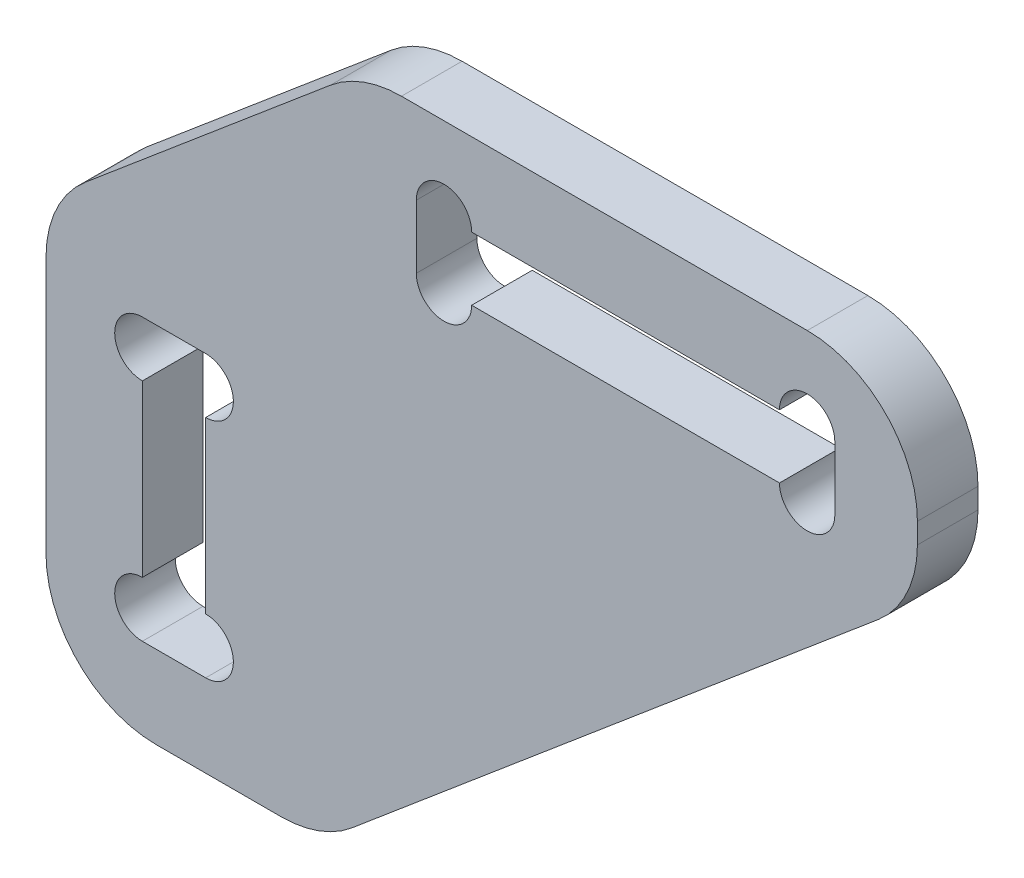
SolidWorks part; units mm, degrees
material "Thornel Mat VMA"
ref_plane "前视基准面" through (0, 0, 0) normal (0, 0, 1) x (1, 0, 0)
ref_plane "上视基准面" through (0, 0, 0) normal (0, 1, 0) x (1, 0, 0)
ref_plane "右视基准面" through (0, 0, 0) normal (1, 0, 0) x (0, 0, -1)
sketch "草图1" plane through (0, 0, 0) normal (0, 0, 1) x (1, 0, 0)
  line L0 (-9.6, 4.15) -> (10.6, 4.15)
  line L1 (7.6, -1.15) -> (-7.6, -1.15)
  line L2 (7.6, -1.15) -> (7.6, 1.15)
  line L3 (7.6, 1.15) -> (-7.6, 1.15)
  line L4 (-7.6, -1.15) -> (-7.6, 1.15)
  line L5 (7.6, -1.15) -> (-7.6, 1.15) construction
  line L6 (7.6, 1.15) -> (-7.6, -1.15) construction
  line L7 (-15.25, -17.7) -> (-17.55, -17.7)
  line L8 (-15.25, -17.7) -> (-15.25, -7.5)
  line L9 (-15.25, -7.5) -> (-17.55, -7.5)
  line L10 (-17.55, -17.7) -> (-17.55, -7.5)
  line L11 (-15.25, -17.7) -> (-17.55, -7.5) construction
  line L12 (-15.25, -7.5) -> (-17.55, -17.7) construction
  line L13 (10.6, 4.15) -> (10.6, -2.4535)
  line L14 (10.6, -2.4535) -> (-11.05, -20.7)
  line L15 (-11.05, -20.7) -> (-21.05, -20.7)
  line L16 (-21.05, -20.7) -> (-21.05, -5.5)
  line L17 (-21.05, -5.5) -> (-9.6, 4.15)
  circle A0 centre (-6.595, -1.15) radius 1.005
  circle A1 centre (6.595, -1.15) radius 1.005
  circle A2 centre (-6.595, 1.15) radius 1.005
  circle A3 centre (6.595, 1.15) radius 1.005
  circle A4 centre (-15.25, -8.505) radius 1.005
  circle A5 centre (-17.55, -8.505) radius 1.005
  circle A6 centre (-17.55, -16.695) radius 1.005
  circle A7 centre (-15.25, -16.695) radius 1.005
  point P0 (0, 0)
  point P6 (-16.4, -12.6)
  dimension "D7" = 2.01
  dimension "D1" = 16.4
  dimension "D2" = 12.6
  dimension "D3" = 2.3
  dimension "D4" = 15.2
  dimension "D5" = 10.2
  dimension "D6" = 2.3
  dimension "D8" = 2
  dimension "D9" = 2
  dimension "D10" = 3
  dimension "D11" = 3.5
  dimension "D12" = 3
  dimension "D13" = 3
  dimension "D14" = 10
extrude "凸台-拉伸1" add sketch "草图1" along normal blind 2.2 contours L17 L16 L15 L14 L13 L0 A7 L7 A6 L10 A5 L9 A4 L8 A3 L2 A1 L1 A0 L4 A2 L3
fillet "圆角1" radius 4 6 edges at (10.6, 4.15, 1.1) (10.6, -2.4535, 1.1) (-11.05, -20.7, 1.1) (-21.05, -20.7, 1.1) (-21.05, -5.5, 1.1) (-9.6, 4.15, 1.1)
